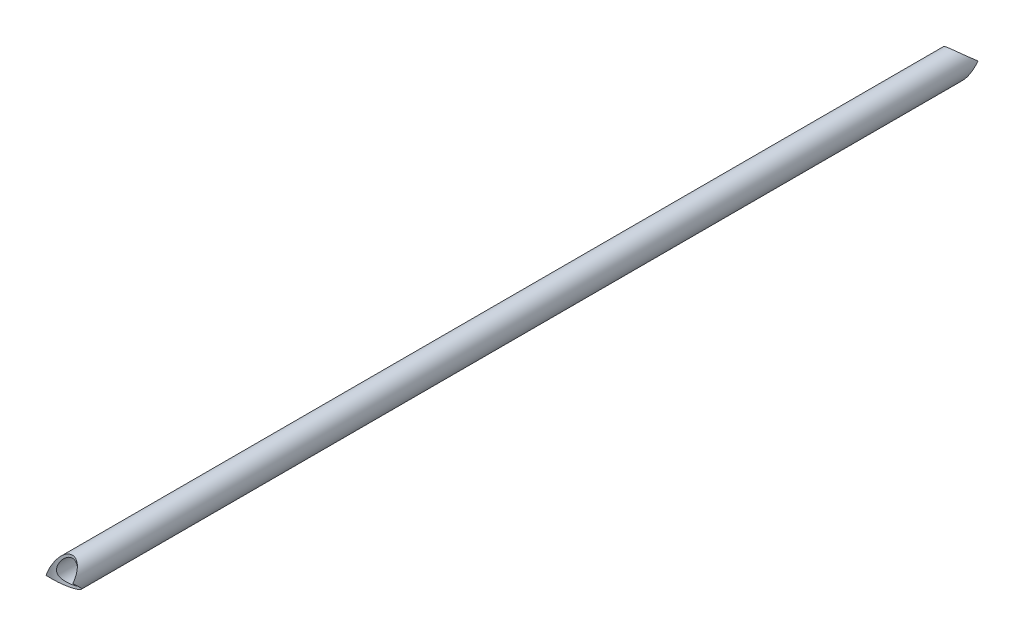
SolidWorks part; units mm, degrees
material "AISI 304"
ref_plane "Plano frontal" through (0, 0, 0) normal (0, 0, 1) x (1, 0, 0)
ref_plane "Plano superior" through (0, 0, 0) normal (0, 1, 0) x (1, 0, 0)
ref_plane "Plano direito" through (0, 0, 0) normal (1, 0, 0) x (0, 0, -1)
ref_plane "Plano1" through (0, 250, 0) normal (0, 1, 0) x (1, 0, 0)
sketch3d "3DSketch1"
  line L0 (803.885, 0, 257.4204) -> (803.885, 0, -257.4204) construction
  line L3 (803.885, 0, -257.4204) -> (0, 0, -200) construction
  line L4 (0, 0, -200) -> (0, 0, 200) construction
  line L5 (0, 0, 200) -> (803.885, 0, 257.4204) construction
sketch "Esboço3" plane through (0, 250, 0) normal (0, 1, 0) x (1, 0, 0)
  line L0 (0, 200) -> (0, -200) construction
  line L1 (0, -200) -> (803.885, -257.4204) construction
  line L2 (803.885, 257.4204) -> (803.885, -257.4204)
  line L3 (803.885, 257.4204) -> (0, 200) construction
sketch "Esboço8" plane through (0, 0, 0) normal (0, 1, 0) x (1, 0, 0)
  line L0 (0, 162.7552) -> (0, -162.7552) construction
  line L1 (0, 0) -> (910, 0) construction
  line L2 (910, 265) -> (910, -265) construction
  line L3 (37.1501, 202.6536) -> (910, 265) construction
  line L4 (37.1501, -202.6536) -> (910, -265) construction
  arc A0 (0, -162.7552) -> (37.1501, -202.6536) centre (40, -162.7552) ccw construction
  arc A1 (0, 162.7552) -> (37.1501, 202.6536) centre (40, 162.7552) cw construction
  point P9 (0, -200)
  point P12 (0, 200)
  dimension "D3" = 40
  dimension "D1" = 400
  dimension "D2" = 910
  dimension "D4" = 530
sketch "Esboço9" plane through (0, 250, 0) normal (0, 1, 0) x (1, 0, 0)
  line L0 (0, 162.7552) -> (0, -162.7552) construction
  line L1 (0, 0) -> (910, 0) construction
  line L2 (910, 265) -> (910, -265) construction
  line L3 (37.1501, 202.6536) -> (910, 265) construction
  line L4 (37.1501, -202.6536) -> (910, -265) construction
  arc A0 (0, -162.7552) -> (37.1501, -202.6536) centre (40, -162.7552) ccw construction
  arc A1 (0, 162.7552) -> (37.1501, 202.6536) centre (40, 162.7552) cw construction
  point P9 (0, -200)
  point P12 (0, 200)
  dimension "D3" = 40
  dimension "D1" = 400
  dimension "D2" = 910
  dimension "D4" = 530
ref_plane "Plano3" through (0, 910, 0) normal (0, 1, 0) x (1, 0, 0)
sketch "Esboço10" plane through (0, 910, 0) normal (0, 1, 0) x (1, 0, 0)
  line L0 (0, 162.4326) -> (0, -163.0779) construction
  line L1 (0, 0) -> (910, 0) construction
  line L2 (910, 265) -> (910, -265) construction
  line L3 (37.1354, 202.3299) -> (910, 265) construction
  line L4 (37.1648, -202.9773) -> (910, -265) construction
  arc A0 (0, -163.0779) -> (37.1648, -202.9773) centre (40, -163.0779) ccw construction
  arc A1 (0, 162.4326) -> (37.1354, 202.3299) centre (40, 162.4326) cw construction
  point P9 (0, -200.3364)
  point P12 (0, 199.6636)
  dimension "D3" = 40
  dimension "D1" = 400
  dimension "D2" = 910
sketch3d "3DSketch3"
  line L0 (910, 0, 265) -> (910, 139.2691, 265)
  line L1 (904.6546, 159.2691, 264.6182) -> (858.6942, 239.0777, 261.3353)
  line L2 (0, 250, 200) -> (803.885, 250, 257.4204) construction
  line L3 (853.5006, 262.564, 260.9643) -> (910, 910, 265)
  line L5 (37.1501, 250, 202.6536) -> (910, 250, 265) construction
  arc A0 (910, 139.2691, 265) -> (904.6546, 159.2691, 264.6182) centre (870.1017, 139.2691, 262.1501) ccw
  arc A1 (858.6942, 239.0777, 261.3353) -> (853.5006, 262.564, 260.9643) centre (893.2472, 259.0777, 263.8034) ccw
  point P10 (910, 149.987, 265)
  point P11 (867.2518, 139.2691, 302.0485)
  point P14 (852.4042, 250, 260.886)
  point P15 (896.097, 259.0777, 223.905)
  point P16 (854.3898, 250, 261.0278)
  dimension "D3" = 40
  dimension "D1" = 150
  dimension "D2" = 145
sketch "Esboço11" plane through (0, 0, 0) normal (0, 1, 0) x (1, 0, 0)
  circle A0 centre (910, -265) radius 7.9375
  dimension "D1" = 15.875
sketch3d "3DSketch4"
  line L0 (910, 0, -265) -> (910, 139.2691, -265)
  line L1 (904.6546, 159.2691, -264.6182) -> (858.6942, 239.0777, -261.3353)
  line L2 (803.885, 250, -257.4204) -> (0, 250, -200) construction
  line L3 (853.5006, 262.564, -260.9643) -> (910, 910, -265)
  line L4 (37.1501, 250, -202.6536) -> (910, 250, -265) construction
  arc A0 (858.6942, 239.0777, -261.3353) -> (853.5006, 262.564, -260.9643) centre (893.2472, 259.0777, -263.8034) ccw
  arc A1 (910, 139.2691, -265) -> (904.6546, 159.2691, -264.6182) centre (870.1017, 139.2691, -262.1501) ccw
  point P10 (852.4042, 250, -260.886)
  point P11 (890.3973, 259.0777, -303.7017)
  point P14 (910, 149.987, -265)
  point P15 (872.9515, 139.2691, -222.2518)
  point P16 (854.3898, 250, -261.0278)
  dimension "D3" = 40
  dimension "D1" = 150
  dimension "D2" = 145
sketch "Esboço12" plane through (0, 0, 0) normal (0, 1, 0) x (1, 0, 0)
  circle A0 centre (910, 265) radius 7.9375
  dimension "D1" = 15.875
sketch "Esboço13" plane through (0, 250, 0) normal (0, 1, 0) x (1, 0, 0)
  line L0 (0, 200) -> (0, -200) construction
  line L1 (0, -200) -> (854.3898, -261.0278) construction
  line L2 (854.3898, -261.0278) -> (854.3898, 261.0278) construction
  line L3 (854.3898, 261.0278) -> (0, 200) construction
  line L4 (854.3898, 261.0278) -> (854.3898, -261.0278)
other "Pipe - configured 21.3 X 2.3(3)"
ref_plane "Plano4" through (854.3898, 250, -261.0278) normal (0, 0, 1) x (1, 0, 0)
sketch "Sketch1" plane through (854.3898, 250, -261.0278) normal (0, 0, 1) x (1, 0, 0)
  circle A0 centre (0, 0) radius 6.4375
  circle A1 centre (0, 0) radius 7.9375
  point P3 (0, 0)
  dimension "Out_dia" = 15.875
  dimension "D1" = 1.5
sweep "Varredura de corte1" cut profiles "Esboço11" path "3DSketch3"
sweep "Varredura de corte2" cut profiles "Esboço12" path "3DSketch4"
